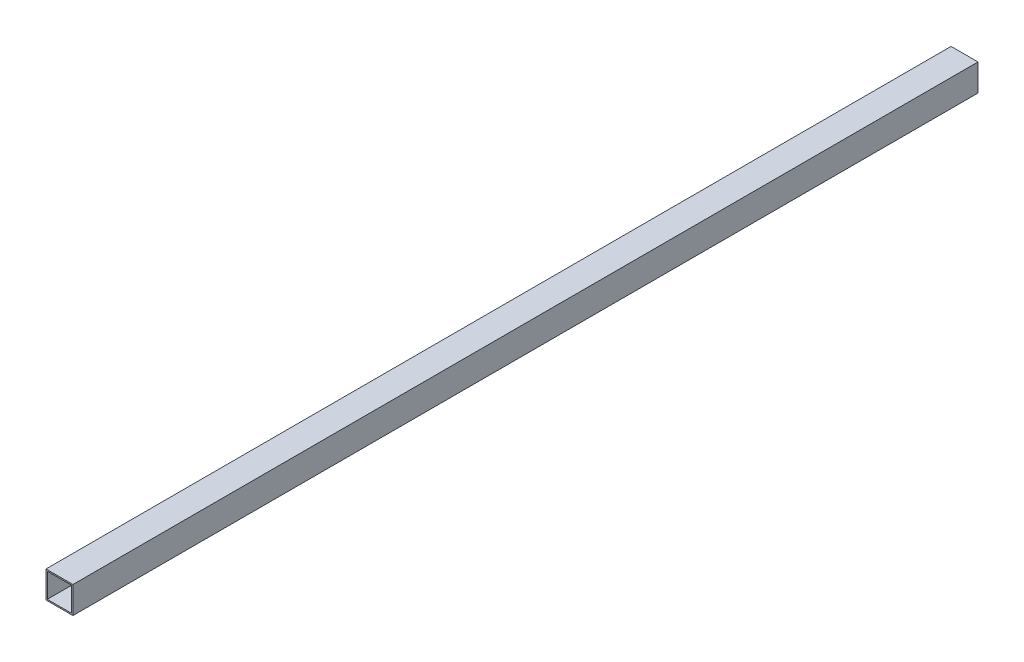
SolidWorks part; units mm, degrees
ref_plane "Front Plane" through (0, 0, 0) normal (0, 0, 1) x (1, 0, 0)
ref_plane "Top Plane" through (0, 0, 0) normal (0, 1, 0) x (1, 0, 0)
ref_plane "Right Plane" through (0, 0, 0) normal (1, 0, 0) x (0, 0, -1)
sketch "Sketch1" plane through (0, 0, 0) normal (0, 0, 1) x (1, 0, 0)
  line L0 (11.3, 11.3) -> (-11.3, 11.3)
  line L1 (12.5, -12.5) -> (-12.5, -12.5)
  line L2 (12.5, -12.5) -> (12.5, 12.5)
  line L3 (12.5, 12.5) -> (-12.5, 12.5)
  line L4 (-12.5, -12.5) -> (-12.5, 12.5)
  line L5 (12.5, -12.5) -> (-12.5, 12.5) construction
  line L6 (12.5, 12.5) -> (-12.5, -12.5) construction
  line L7 (-11.3, -11.3) -> (-11.3, 11.3)
  line L8 (11.3, -11.3) -> (-11.3, -11.3)
  line L9 (11.3, -11.3) -> (11.3, 11.3)
  point P0 (0, 0)
  dimension "D1" = 25
  dimension "D2" = 25
  dimension "D3" = 1.2
extrude "Boss-Extrude1" add sketch "Sketch1" along normal blind 840
